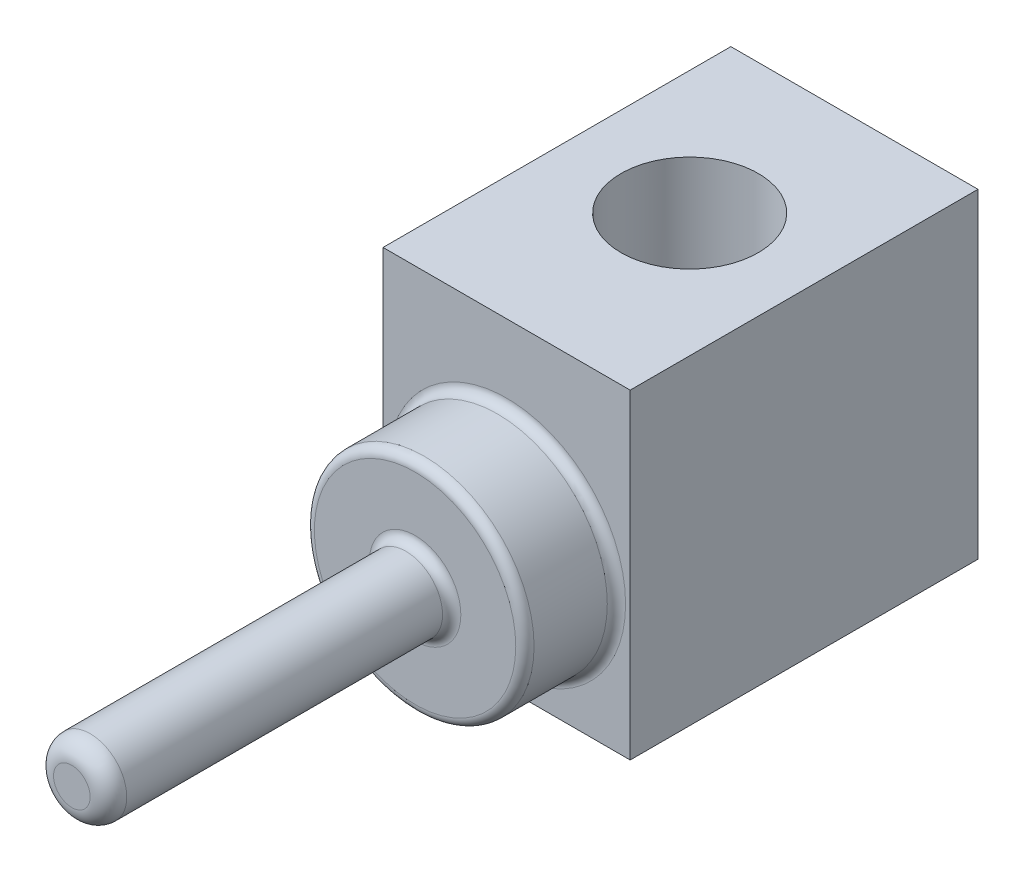
SolidWorks part; units mm, degrees
ref_plane "Спереди" through (0, 0, 0) normal (0, 0, 1) x (1, 0, 0)
ref_plane "Сверху" through (0, 0, 0) normal (0, 1, 0) x (1, 0, 0)
ref_plane "Справа" through (0, 0, 0) normal (1, 0, 0) x (0, 0, -1)
sketch "Эскиз1" plane through (0, 0, 0) normal (0, 0, 1) x (1, 0, 0)
  line L1 (-1.35, 1.75) -> (1.35, 1.75)
  line L2 (-1.35, 1.75) -> (-1.35, -1.75)
  line L3 (-1.35, -1.75) -> (1.35, -1.75)
  line L4 (1.35, 1.75) -> (1.35, -1.75)
  line L5 (-1.35, 1.75) -> (1.35, -1.75) construction
  line L6 (-1.35, -1.75) -> (1.35, 1.75) construction
  point P0 (0, 0)
  dimension "D1" = 2.7
  dimension "D2" = 3.5
extrude "Бобышка-Вытянуть1" add sketch "Эскиз1" against normal blind 3.8
sketch "Эскиз2" plane through (0, 0, 0) normal (0, 0, 1) x (1, 0, 0)
  line L0 (-1.35, -0.3) -> (1.35, -0.3) construction
  line L1 (0, 1.75) -> (0, -1.75) construction
  line L4 (1.35, -1.75) -> (1.35, 1.75)
  line L5 (1.35, 1.75) -> (-1.35, 1.75)
  line L6 (-1.35, 1.75) -> (-1.35, -1.75)
  line L7 (-1.35, -1.75) -> (1.35, -1.75)
  line L8 (1.35, -1.75) -> (1.35, 1.75)
  line L9 (1.35, 1.75) -> (-1.35, 1.75)
  line L10 (-1.35, 1.75) -> (-1.35, -1.75)
  line L11 (-1.35, -1.75) -> (1.35, -1.75)
  circle A0 centre (0, -0.3) radius 1
  dimension "D3" = 2
  dimension "D1" = 0
  dimension "D2" = 1.45
extrude "Вырез-Вытянуть1" cut sketch "Эскиз2" against normal through all flip side to cut
sketch "Эскиз4" plane through (0, 1.75, 0) normal (0, 1, 0) x (1, 0, 0)
  line L4 (-1.35, 0) -> (1.35, 0)
  line L5 (1.35, 0) -> (1.35, 3.8)
  line L6 (1.35, 3.8) -> (-1.35, 3.8)
  line L7 (-1.35, 3.8) -> (-1.35, 0)
  line L8 (-1.35, 0) -> (1.35, 0)
  line L9 (1.35, 0) -> (1.35, 3.8)
  line L10 (1.35, 3.8) -> (-1.35, 3.8)
  line L11 (-1.35, 3.8) -> (-1.35, 0)
  line L12 (-1.35, 2) -> (1.35, 2) construction
  circle A0 centre (0, 2) radius 0.75
  dimension "D3" = 1.5
  dimension "D1" = 0
  dimension "D2" = 2
extrude "Вырез-Вытянуть2" cut sketch "Эскиз4" against normal blind 1.85 flip side to cut
sketch "Эскиз7" plane through (0, 0, 0) normal (0, 0, 1) x (1, 0, 0)
  circle A0 centre (0, -0.3) radius 1.2
  dimension "D1" = 2.4
extrude "Бобышка-Вытянуть3" add sketch "Эскиз7" along normal blind 1
sketch "Эскиз8" plane through (0, 0, 1) normal (0, 0, 1) x (1, 0, 0)
  circle A0 centre (0, -0.3) radius 0.4
  dimension "D1" = 0.8
extrude "Бобышка-Вытянуть4" add sketch "Эскиз8" along normal blind 3.75
fillet "Скругление1" radius 0.1 1 edges at (1.2, -0.3, 1)
fillet "Скругление2" radius 0.1 1 edges at (1.2, -0.3, 0)
fillet "Скругление3" radius 0.1 1 edges at (0.4, -0.3, 1)
fillet "Скругление4" radius 0.2 1 edges at (0.4, -0.3, 4.75)
